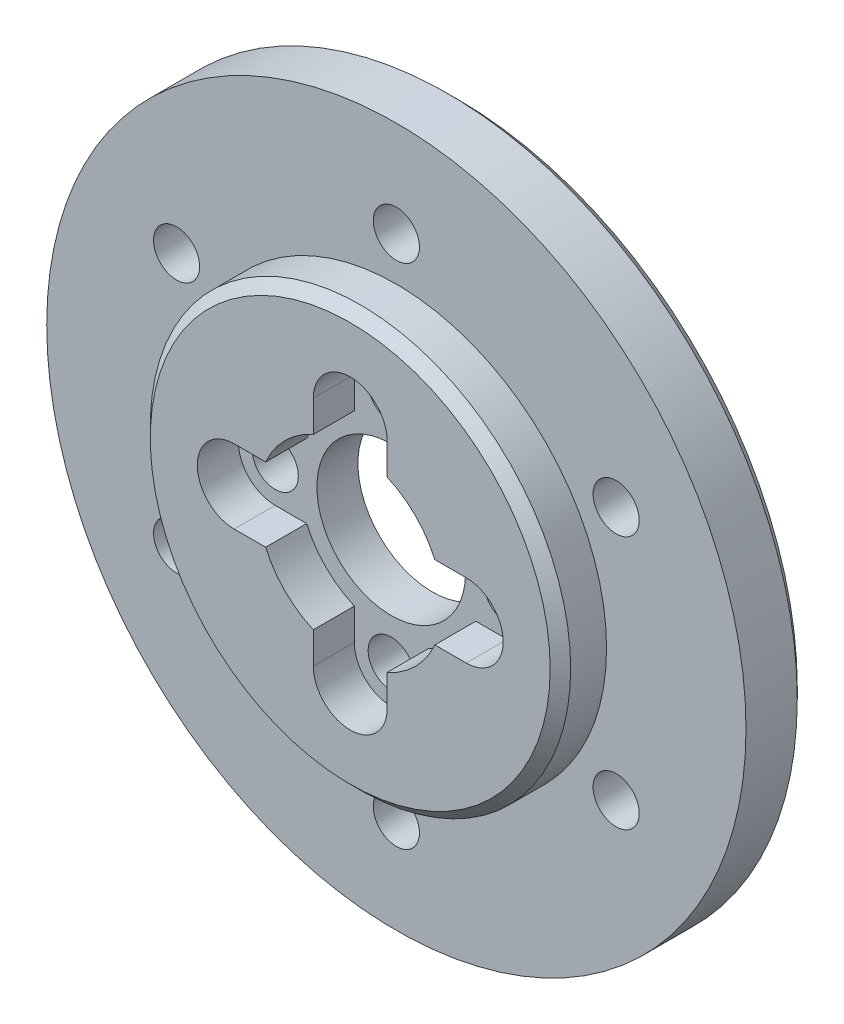
SolidWorks part; units mm, degrees
material "6061-T6 (SS)"
ref_plane "Front Plane" through (0, 0, 0) normal (0, 0, 1) x (1, 0, 0)
ref_plane "Top Plane" through (0, 0, 0) normal (0, 1, 0) x (1, 0, 0)
ref_plane "Right Plane" through (0, 0, 0) normal (1, 0, 0) x (0, 0, -1)
sketch "Sketch1" plane through (0, 0, 0) normal (0, 0, 1) x (1, 0, 0)
  circle A0 centre (0, 0) radius 34.1
  dimension "D1" = 68.2
extrude "Boss-Extrude1" add sketch "Sketch1" along normal mid plane 3.5
sketch "Sketch4" plane through (0, 0, 1.75) normal (0, 0, 1) x (1, 0, 0)
  circle A0 centre (0, 0) radius 28.5
  dimension "D1" = 57
extrude "Boss-Extrude2" add sketch "Sketch4" along normal blind 2
sketch "Sketch5" plane through (0, 0, -1.75) normal (0, 0, -1) x (-1, 0, 0)
  circle A0 centre (0, 0) radius 16.25
  circle A1 centre (0, 0) radius 34.1 construction
  circle A2 centre (0, 0) radius 34.1
  dimension "D1" = 32.5
extrude "Boss-Extrude3" add sketch "Sketch5" along normal blind 2.5
sketch "Sketch3" plane through (0, 0, 1.75) normal (0, 0, 1) x (1, 0, 0)
  circle A8 centre (0, 0) radius 11.3137 construction
  circle A9 centre (0, 11.3137) radius 2.25
  circle A11 centre (11.3137, 0) radius 2.25
  circle A13 centre (0, -11.3137) radius 2.25
  circle A15 centre (-11.3137, 0) radius 2.25
  point P21 (0, 0)
  dimension "D3" = 22.6274
  dimension "D4" = 4.5
  dimension "D5" = 4
extrude "Cut-Extrude2" cut sketch "Sketch3" against normal through all both and the other way through all
sketch "Sketch2" plane through (0, 0, 1.75) normal (0, 0, 1) x (1, 0, 0)
  circle A0 centre (0, 0) radius 7.25
  dimension "D1" = 14.5
extrude "Cut-Extrude1" cut sketch "Sketch2" along normal through all both and the other way through all
sketch "Sketch7" plane through (0, 0, 3.75) normal (0, 0, 1) x (1, 0, 0)
  circle A0 centre (0, 0) radius 20.5
  circle A5 centre (0, -11.3137) radius 2.25 construction
  circle A6 centre (11.3137, 0) radius 2.25 construction
  circle A7 centre (0, 11.3137) radius 2.25 construction
  circle A8 centre (-11.3137, 0) radius 2.25 construction
  circle A9 centre (0, 0) radius 7.25 construction
  circle A10 centre (0, -11.3137) radius 2.25
  circle A11 centre (11.3137, 0) radius 2.25
  circle A12 centre (0, 11.3137) radius 2.25
  circle A13 centre (-11.3137, 0) radius 2.25
  circle A14 centre (0, 0) radius 7.25
  dimension "D1" = 41
extrude "Boss-Extrude4" add sketch "Sketch7" along normal blind 2.5
sketch "Sketch8" plane through (0, 0, 1.75) normal (0, 0, 1) x (1, 0, 0)
  circle A0 centre (0, 0) radius 28.5 construction
  circle A1 centre (0, 0) radius 34.1
  circle A2 centre (0, 0) radius 34.1
  circle A3 centre (0, 0) radius 28.5
  dimension "D1" = 0
extrude "Boss-Extrude5" add sketch "Sketch8" along normal up to surface (2 mm away) up to face at (20.5, 0, 3.75)
sketch "Sketch10" plane through (0, 0, 3.75) normal (0, 0, 1) x (1, 0, 0)
  circle A0 centre (0, 0) radius 20.5 construction
  circle A1 centre (0, 0) radius 34.1
  circle A2 centre (0, 0) radius 34.1
  circle A3 centre (0, 0) radius 20.5
  dimension "D1" = 0
extrude "Cut-Extrude4" cut sketch "Sketch10" against normal blind 2
sketch "Sketch11" plane through (0, 0, 6.25) normal (0, 0, 1) x (1, 0, 0)
  line L0 (-11.3137, 3.6) -> (-8.2486, 3.6)
  line L1 (-3.6, 8.2486) -> (-3.6, 11.3137)
  line L2 (3.6, 11.3137) -> (3.6, 8.2486)
  line L3 (8.2486, 3.6) -> (11.3137, 3.6)
  line L4 (11.3137, -3.6) -> (8.2486, -3.6)
  line L5 (3.6, -8.2486) -> (3.6, -11.3137)
  line L6 (-3.6, -11.3137) -> (-3.6, -8.2486)
  line L7 (-8.2486, -3.6) -> (-11.3137, -3.6)
  circle A0 centre (-11.3137, 0) radius 2.25 construction
  circle A1 centre (0, -11.3137) radius 2.25 construction
  circle A2 centre (11.3137, 0) radius 2.25 construction
  circle A3 centre (0, 11.3137) radius 2.25 construction
  circle A4 centre (-11.3137, 0) radius 2.25 construction
  circle A5 centre (0, -11.3137) radius 2.25 construction
  circle A6 centre (11.3137, 0) radius 2.25 construction
  circle A7 centre (0, 11.3137) radius 2.25 construction
  arc A8 (-3.6, -11.3137) -> (3.6, -11.3137) centre (0, -11.3137) ccw
  arc A9 (11.3137, -3.6) -> (11.3137, 3.6) centre (11.3137, 0) ccw
  arc A10 (3.6, 11.3137) -> (-3.6, 11.3137) centre (0, 11.3137) ccw
  arc A11 (-11.3137, 3.6) -> (-11.3137, -3.6) centre (-11.3137, 0) ccw
  arc A12 (-8.2486, -3.6) -> (-3.6, -8.2486) centre (0, 0) ccw
  arc A13 (-3.6, 8.2486) -> (-8.2486, 3.6) centre (0, 0) ccw
  arc A14 (8.2486, 3.6) -> (3.6, 8.2486) centre (0, 0) ccw
  arc A15 (3.6, -8.2486) -> (8.2486, -3.6) centre (0, 0) ccw
  dimension "D1" = 7.2
  dimension "D2" = 18
extrude "Cut-Extrude5" cut sketch "Sketch11" against normal blind 4
sketch "Sketch6" plane through (0, 0, -4.25) normal (0, 0, 1) x (1, 0, 0)
  circle A0 centre (0, 24.75) radius 2.25
  dimension "D1" = 4.5
  dimension "D2" = 24.75
extrude "Cut-Extrude3" cut sketch "Sketch6" against normal through all both and the other way through all
sketch "Sketch12" plane through (0, 0, -4.25) normal (0, 0, -1) x (-1, 0, 0)
  circle A0 centre (0, 24.75) radius 2.25 construction
  circle A1 centre (0, 24.75) radius 2.25 construction
  circle A2 centre (0, 24.75) radius 3.75
  dimension "D1" = 7.5
extrude "Cut-Extrude6" cut sketch "Sketch12" against normal blind 2
pattern_circular "CirPattern1" count 6 over 360 about axis through (0, 0, 0) along (0, 0, 1) of "Cut-Extrude3", "Cut-Extrude6"
chamfer "Chamfer1" distance 1 angle 45 2 edges at (-34.1, 0, -4.25) (20.5, 0, 6.25)
